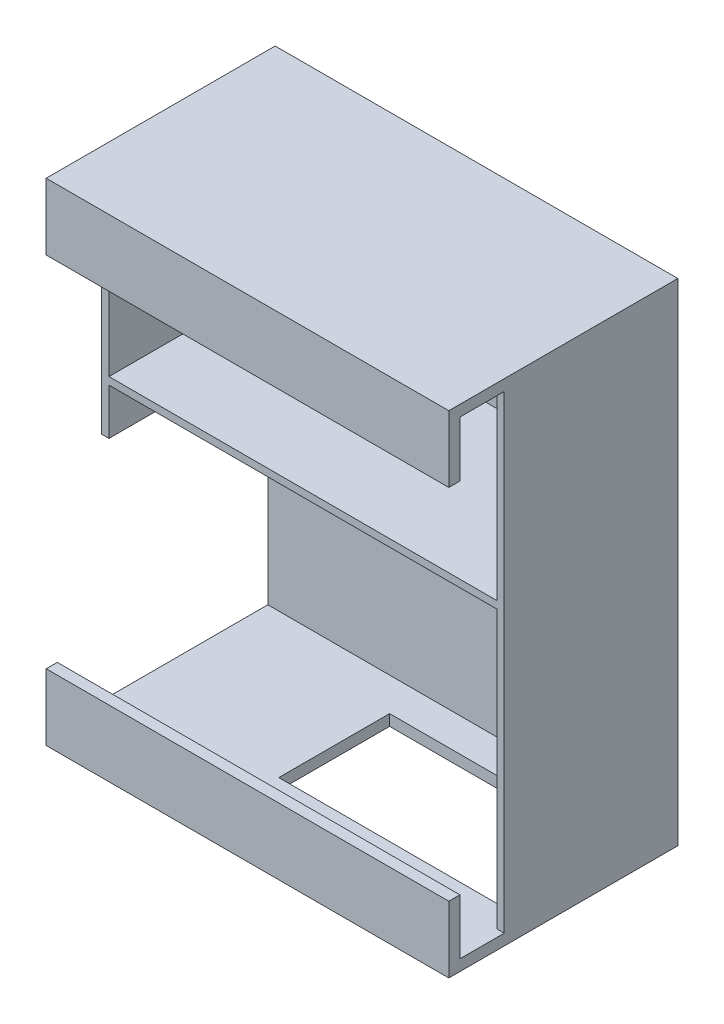
SolidWorks part; units mm, degrees
ref_plane "Front Plane" through (0, 0, 0) normal (0, 0, 1) x (1, 0, 0)
ref_plane "Top Plane" through (0, 0, 0) normal (0, 1, 0) x (1, 0, 0)
ref_plane "Right Plane" through (0, 0, 0) normal (1, 0, 0) x (0, 0, -1)
sketch "Sketch1" plane through (0, 0, 0) normal (0, 0, 1) x (1, 0, 0)
  line L1 (-54.5, -66.5) -> (54.5, -66.5)
  line L2 (-54.5, -66.5) -> (-54.5, 66.5)
  line L3 (-54.5, 66.5) -> (54.5, 66.5)
  line L4 (54.5, -66.5) -> (54.5, 66.5)
  line L5 (-54.5, -66.5) -> (54.5, 66.5) construction
  line L6 (-54.5, 66.5) -> (54.5, -66.5) construction
  point P0 (0, 0)
  dimension "D1" = 133
  dimension "D2" = 109
extrude "Boss-Extrude1" add sketch "Sketch1" along normal blind 62
sketch "Sketch2" plane through (-54.5, 0, 0) normal (-1, 0, 0) x (0, 0, 1)
  line L0 (62, 66.5) -> (62, -66.5) construction
  line L1 (0, 66.5) -> (0, -66.5) construction
  line L2 (62, 66.5) -> (0, 66.5) construction
  line L3 (62, -66.5) -> (0, -66.5) construction
  line L4 (62, 66.5) -> (62, 38.5)
  line L5 (62, 38.5) -> (62, 66.5)
  line L6 (62, -66.5) -> (62, -38.5)
  line L7 (62, -38.5) -> (62, -66.5)
  line L8 (62, 38.5) -> (59, 38.5)
  line L9 (59, 38.5) -> (62, 38.5)
  dimension "D1" = 62
  dimension "D2" = 133
  dimension "D3" = 28
  dimension "D4" = 28
  dimension "D5" = 3
sketch "Sketch3" plane through (-54.5, 0, 0) normal (-1, 0, 0) x (0, 0, 1)
  line L1 (59, 38.5) -> (62, 38.5)
  line L2 (59, 38.5) -> (59, -38.5)
  line L3 (59, -38.5) -> (62, -38.5)
  line L4 (62, 38.5) -> (62, -38.5)
extrude "Cut-Extrude2" cut sketch "Sketch3" against normal blind 109
sketch "Sketch4" plane through (-54.5, 0, 0) normal (-1, 0, 0) x (0, 0, 1)
  line L2 (59, 63.5) -> (47, 63.5)
  line L6 (59, -63.5) -> (47, -63.5)
  line L10 (59, -63.5) -> (59, 63.5)
  line L12 (47, -63.5) -> (47, 63.5)
  dimension "D2" = 12
extrude "Cut-Extrude3" cut sketch "Sketch4" against normal blind 109
sketch "Sketch5" plane through (-54.5, 0, 0) normal (-1, 0, 0) x (0, 0, 1)
  line L1 (47, -63.5) -> (2, -63.5)
  line L2 (47, -63.5) -> (47, 1.5)
  line L3 (47, 1.5) -> (2, 1.5)
  line L4 (2, -63.5) -> (2, 1.5)
  dimension "D1" = 45
  dimension "D2" = 65
extrude "Cut-Extrude4" cut sketch "Sketch5" against normal blind 107
sketch "Sketch6" plane through (0, 0, 47) normal (0, 0, 1) x (1, 0, 0)
  line L1 (52.5, 1.5) -> (-52.5, 1.5)
  line L2 (52.5, 1.5) -> (52.5, 11.5)
  line L3 (52.5, 11.5) -> (-52.5, 11.5)
  line L4 (-52.5, 1.5) -> (-52.5, 11.5)
  dimension "D1" = 105
  dimension "D2" = 10
extrude "Cut-Extrude5" cut sketch "Sketch6" against normal blind 45
sketch "Sketch7" plane through (0, 0, 47) normal (0, 0, 1) x (1, 0, 0)
  line L3 (-52.5, 13.5) -> (52.5, 13.5)
  line L4 (-52.5, 13.5) -> (-52.5, 63.5)
  line L5 (-52.5, 63.5) -> (52.5, 63.5)
  line L6 (52.5, 13.5) -> (52.5, 63.5)
  dimension "D1" = 50
  dimension "D2" = 105
extrude "Cut-Extrude6" cut sketch "Sketch7" against normal blind 45
sketch "Sketch9" plane through (0, 0, 0) normal (0, 0, -1) x (-1, 0, 0)
  line L6 (-52.5, 54.5) -> (52.5, 54.5)
  line L7 (-52.5, 54.5) -> (-52.5, 22.5)
  line L8 (-52.5, 22.5) -> (52.5, 22.5)
  line L9 (52.5, 54.5) -> (52.5, 22.5)
  dimension "D1" = 105
  dimension "D4" = 32
extrude "Cut-Extrude7" cut sketch "Sketch9" against normal blind 45
sketch "Sketch10" plane through (0, -66.5, 0) normal (0, -1, 0) x (1, 0, 0)
  line L9 (52.5, 11.0226) -> (-12.5, 11.0226)
  line L10 (52.5, 11.0226) -> (52.5, 41.0226)
  line L11 (52.5, 41.0226) -> (-12.5, 41.0226)
  line L12 (-12.5, 11.0226) -> (-12.5, 41.0226)
  point P0 (-60.909, 58.4971)
  dimension "D3" = 30
  dimension "D4" = 65
sketch "Sketch11" plane through (-54.5, 0, 0) normal (-1, 0, 0) x (0, 0, 1)
  line L1 (62, 38.5) -> (59, 38.5) construction
  line L2 (62, 66.5) -> (0, 66.5) construction
  line L3 (62, -66.5) -> (0, -66.5) construction
  line L4 (59, -38.5) -> (62, -38.5) construction
  line L5 (62, 66.5) -> (62, 38.5) construction
  line L6 (59, 38.5) -> (62, 38.5)
  line L7 (59, 38.5) -> (59, 48.5)
  line L8 (59, 48.5) -> (62, 48.5)
  line L9 (62, 38.5) -> (62, 48.5)
  line L10 (59, 63.5) -> (47, 63.5) construction
  line L11 (2, -63.5) -> (59, -63.5) construction
  line L12 (62, -66.5) -> (62, -38.5) construction
  line L13 (59, -38.5) -> (62, -38.5)
  line L14 (59, -38.5) -> (59, -48.5)
  line L15 (59, -48.5) -> (62, -48.5)
  line L16 (62, -38.5) -> (62, -48.5)
  dimension "D1" = 28
  dimension "D2" = 28
  dimension "D3" = 127
  dimension "5" = 10
  dimension "D4" = 10
extrude "Cut-Extrude9" cut sketch "Sketch11" against normal blind 192
extrude "Cut-Extrude10" cut sketch "Sketch10" against normal blind 10 contours L11 L12 L9 L10
sketch "Sketch14" plane through (0, 1.5, 0) normal (0, -1, 0) x (1, 0, 0)
  line L0 (-54.5, 47) -> (-54.5, 2)
  line L1 (-54.5, 2) -> (-52.5, 2)
  line L2 (-52.5, 2) -> (-52.5, 47)
  line L3 (-52.5, 2) -> (-52.5, 47) construction
  line L4 (-52.5, 47) -> (-54.5, 47) construction
  line L5 (-52.5, 47) -> (-54.5, 47)
extrude "Boss-Extrude2" add sketch "Sketch14" along normal blind 2.5
